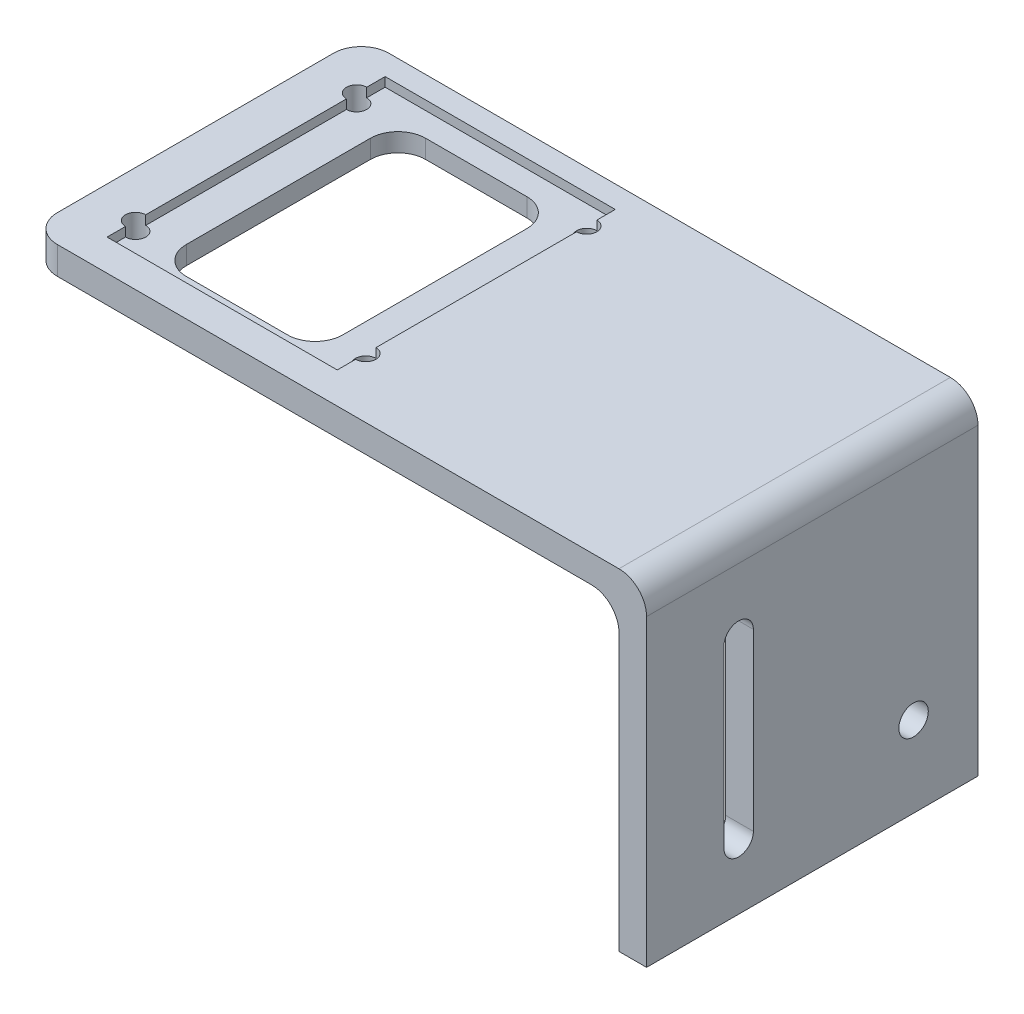
SolidWorks part; units mm, degrees
ref_plane "前视基准面" through (0, 0, 0) normal (0, 0, 1) x (1, 0, 0)
ref_plane "上视基准面" through (0, 0, 0) normal (0, 1, 0) x (1, 0, 0)
ref_plane "右视基准面" through (0, 0, 0) normal (1, 0, 0) x (0, 0, -1)
sketch "草图1" plane through (0, 0, 0) normal (0, 0, 1) x (1, 0, 0)
  line L1 (0, 0) -> (67, 0)
  line L2 (0, 0) -> (0, -3)
  line L3 (0, -3) -> (64, -3)
  line L4 (67, 0) -> (67, -2)
  line L6 (67, -2) -> (67, -36)
  line L7 (67, -36) -> (64, -36)
  line L8 (64, -3) -> (64, -36)
  dimension "D1" = 67
  dimension "D2" = 3
  dimension "D3" = 36
  dimension "D4" = 3
extrude "凸台-拉伸1" add sketch "草图1" along normal blind 36
sketch "草图2" plane through (0, 0, 0) normal (0, 1, 0) x (1, 0, 0)
  line L0 (67, 0) -> (0, 0) construction
  line L1 (0, -36) -> (0, 0) construction
  line L2 (67, -36) -> (0, -36) construction
  line L3 (9, -5) -> (26, -5)
  line L4 (9, -5) -> (9, -31)
  line L5 (9, -31) -> (26, -31)
  line L6 (26, -5) -> (26, -31)
  circle A0 centre (5, -5.5) radius 1.1
  circle A1 centre (5, -29.5) radius 1.1
  circle A2 centre (30, -5.5) radius 1.1
  circle A3 centre (30, -29.5) radius 1.1
  dimension "D1" = 2
  dimension "D3" = 5.5
  dimension "D4" = 5
  dimension "D9" = 25
  dimension "D5" = 5
  dimension "D6" = 5
  dimension "D7" = 4
  dimension "D8" = 4
  dimension "D2" = 2
extrude "切除-拉伸1" cut sketch "草图2" against normal blind 12
sketch "草图3" plane through (64, 0, 0) normal (-1, 0, 0) x (0, 0, 1)
  line L0 (36, -3) -> (36, -36) construction
  line L1 (36, -3) -> (0, -3) construction
  line L2 (36, -36) -> (0, -36) construction
  line L3 (27.6, -10) -> (27.6, -29)
  line L4 (24.4, -10) -> (24.4, -29)
  arc A0 (27.6, -10) -> (24.4, -10) centre (26, -10) ccw
  arc A1 (24.4, -29) -> (27.6, -29) centre (26, -29) ccw
  circle A3 centre (7, -27.2152) radius 1.6
  dimension "D1" = 10
  dimension "D2" = 7
  dimension "D3" = 7
  dimension "D4" = 17.4
extrude "切除-拉伸2" cut sketch "草图3" against normal blind 22
fillet "圆角1" radius 3 8 edges at (0, -1.5, 0) (0, -1.5, 36) (26, -1.5, 31) (9, -1.5, 31) (26, -1.5, 5) (9, -1.5, 5) (64, -3, 18) (67, 0, 18)
sketch "草图4" plane through (0, 0, 0) normal (0, 1, 0) x (1, 0, 0)
  line L2 (5, -4.4) -> (5, -30.6)
  line L4 (30, -4.4) -> (30, -30.6)
  line L6 (5, -4.4) -> (5, -2.4)
  line L7 (5, -2.4) -> (30, -2.4)
  line L8 (30, -4.4) -> (30, -2.4)
  line L10 (5, -30.6) -> (5, -32.6)
  line L11 (5, -32.6) -> (30, -32.6)
  line L12 (30, -30.6) -> (30, -32.6)
  circle A0 centre (5, -5.5) radius 1.1 construction
  circle A1 centre (30, -29.5) radius 1.1 construction
  dimension "D1" = 2
  dimension "D2" = 2
extrude "切除-拉伸3" cut sketch "草图4" against normal blind 1
